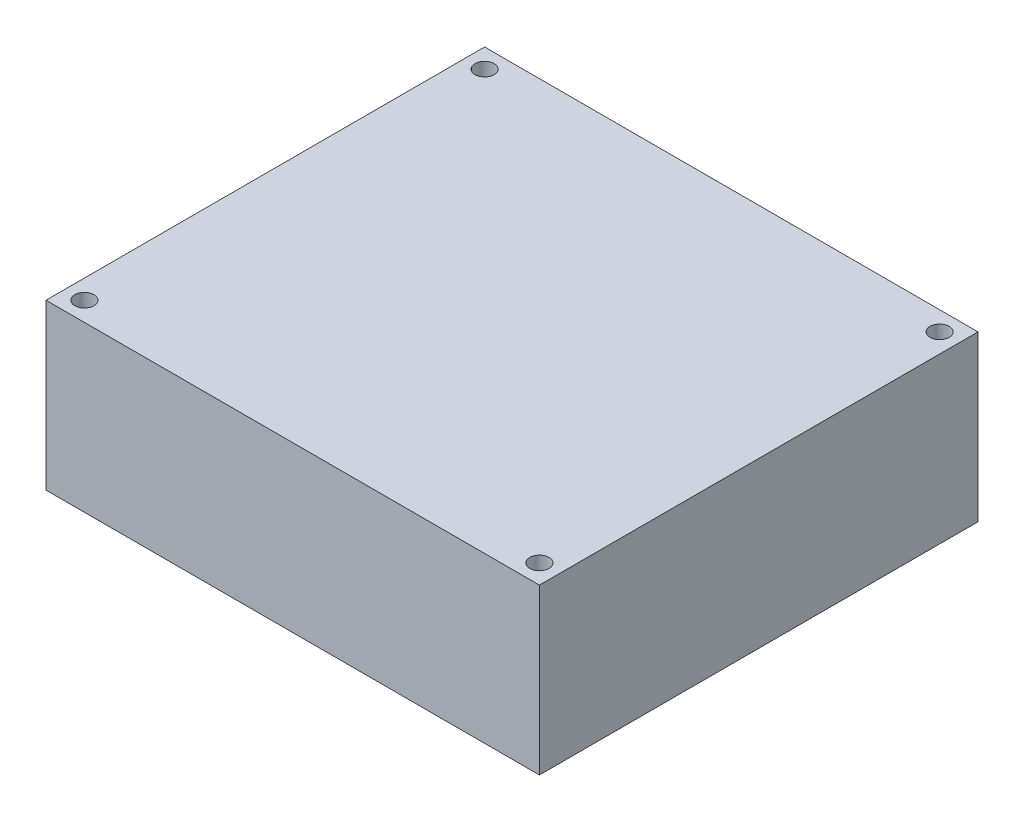
SolidWorks part; units mm, degrees
ref_plane "前视基准面" through (0, 0, 0) normal (0, 0, 1) x (1, 0, 0)
ref_plane "上视基准面" through (0, 0, 0) normal (0, 1, 0) x (1, 0, 0)
ref_plane "右视基准面" through (0, 0, 0) normal (1, 0, 0) x (0, 0, -1)
sketch "草图1" plane through (0, 0, 0) normal (0, 1, 0) x (1, 0, 0)
  line L1 (-45, -40) -> (45, -40)
  line L2 (-45, -40) -> (-45, 40)
  line L3 (-45, 40) -> (45, 40)
  line L4 (45, -40) -> (45, 40)
  line L5 (-45, -40) -> (45, 40) construction
  line L6 (-45, 40) -> (45, -40) construction
  circle A0 centre (-41.5, 36.5) radius 1.75
  circle A1 centre (41.5, 36.5) radius 1.75
  circle A2 centre (41.5, -36.5) radius 1.75
  circle A3 centre (-41.5, -36.5) radius 1.75
  point P0 (0, 0)
  dimension "D3" = 3.5
  dimension "D4" = 3.5
  dimension "D5" = 3.5
  dimension "D6" = 3.5
  dimension "D7" = 3.5
  dimension "D8" = 3.5
  dimension "D9" = 3.5
  dimension "D10" = 3.5
  dimension "D11" = 3.5
  dimension "D1" = 90
  dimension "D2" = 80
extrude "凸台-拉伸1" add sketch "草图1" along normal blind 30
